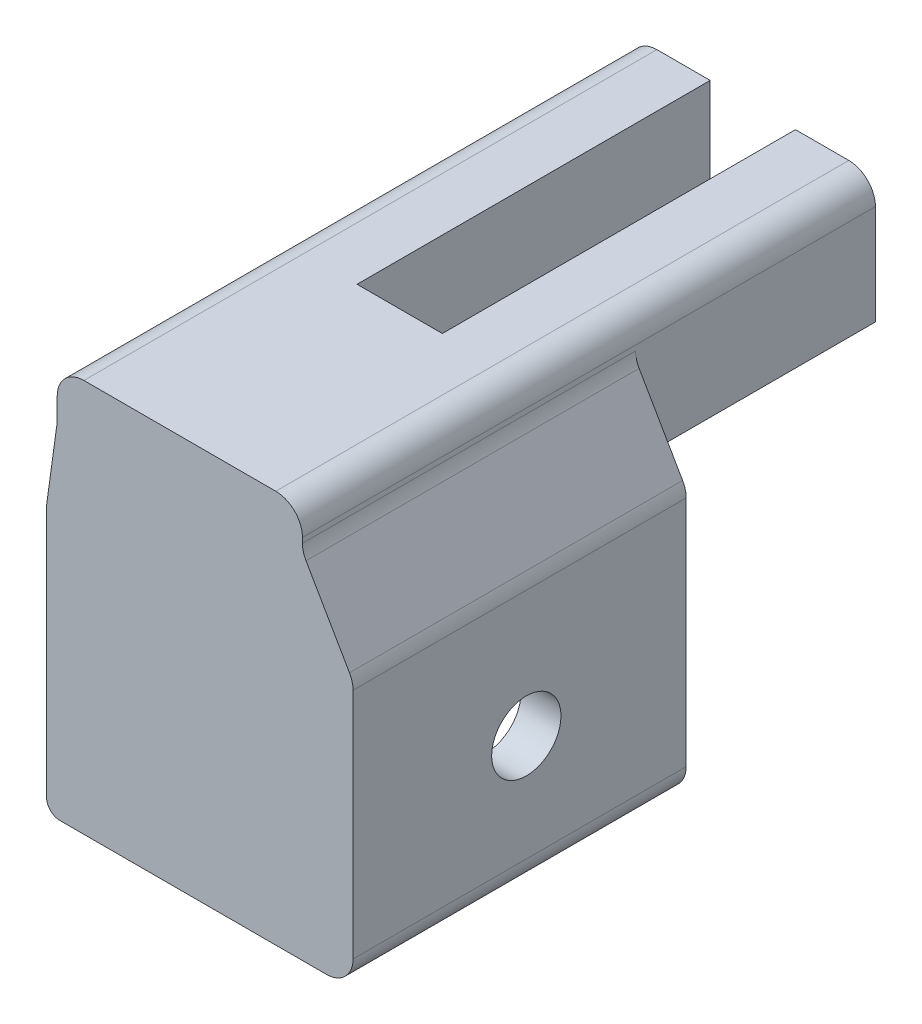
SolidWorks part; units mm, degrees
ref_plane "正面" through (0, 0, 0) normal (0, 0, 1) x (1, 0, 0)
ref_plane "平面" through (0, 0, 0) normal (0, 1, 0) x (1, 0, 0)
ref_plane "右側面" through (0, 0, 0) normal (1, 0, 0) x (0, 0, -1)
sketch "ｽｹｯﾁ1" plane through (0, 0, 0) normal (0, 0, 1) x (1, 0, 0)
  line L1 (-10, 10) -> (10, 10)
  line L2 (-10, 10) -> (-10, -10)
  line L3 (-10, -10) -> (10, -10)
  line L4 (10, 10) -> (10, -10)
  line L5 (-10, 10) -> (10, -10) construction
  line L6 (-10, -10) -> (10, 10) construction
  point P0 (0, 0)
  dimension "D1" = 20
extrude "ﾎﾞｽ - 押し出し1" add sketch "ｽｹｯﾁ1" along normal blind 3
sketch "ｽｹｯﾁ2" plane through (0, 0, 0) normal (0, 0, -1) x (-1, 0, 0)
  line L0 (-10, 10) -> (10, 10) construction
  line L1 (-3.5, 4) -> (3.5, 4)
  line L2 (-3.5, 4) -> (-3.5, 10)
  line L3 (-3.5, 10) -> (3.5, 10)
  line L4 (3.5, 4) -> (3.5, 10)
  line L5 (-3.5, 4) -> (3.5, 10) construction
  line L6 (-3.5, 10) -> (3.5, 4) construction
  line L7 (0, 0) -> (0, 7) construction
  point P0 (0, 7)
  dimension "D1" = 6
  dimension "D2" = 7
extrude "ﾎﾞｽ - 押し出し2" add sketch "ｽｹｯﾁ2" along normal blind 40
sketch "ｽｹｯﾁ3" plane through (0, 0, 3) normal (0, 0, 1) x (1, 0, 0)
  line L0 (-10, -10) -> (10, -10) construction
  line L1 (10, 10) -> (13, 10)
  line L2 (10, 10) -> (10, -10)
  line L3 (10, -10) -> (13, -10)
  line L4 (13, 10) -> (13, -10)
  dimension "D1" = 3
extrude "ﾎﾞｽ - 押し出し3" add sketch "ｽｹｯﾁ3" against normal blind 25
sketch "ｽｹｯﾁ4" plane through (13, 0, 0) normal (1, 0, 0) x (0, 0, -1)
  line L0 (0, 0) -> (22, 0) construction
  line L1 (22, -10) -> (22, 10) construction
  circle A0 centre (10, 0) radius 2.6
  dimension "D1" = 10
  dimension "D2" = 5.2
extrude "ｶｯﾄ - 押し出し1" cut sketch "ｽｹｯﾁ4" against normal up to next
fillet "ﾌｨﾚｯﾄ1" radius 1 1 edges at (-10, -10, 1.5)
ref_plane "平面1" through (0, 0, -13.5) normal (0, 0, -1) x (-1, 0, 0)
sketch "ｽｹｯﾁ5" plane through (0, 0, -13.5) normal (0, 0, -1) x (-1, 0, 0)
  line L0 (3.5, 10) -> (-3.5, 10) construction
  line L1 (-1.6, 6.1) -> (1.6, 6.1)
  line L2 (-1.6, 6.1) -> (-1.6, 10)
  line L3 (-1.6, 10) -> (1.6, 10)
  line L4 (1.6, 6.1) -> (1.6, 10)
  line L5 (-1.6, 6.1) -> (1.6, 10) construction
  line L6 (-1.6, 10) -> (1.6, 6.1) construction
  line L7 (0, 8.05) -> (0, 0) construction
  point P0 (0, 8.05)
  dimension "D1" = 3.2
  dimension "D2" = 3.9
extrude "ｶｯﾄ - 押し出し2" cut sketch "ｽｹｯﾁ5" along normal blind 30
sketch "ｽｹｯﾁ6" plane through (0, 0, 3) normal (0, 0, 1) x (1, 0, 0)
  line L0 (13, 10) -> (-10, 10) construction
  line L1 (3.2, 10) -> (9.2, 10)
  line L2 (3.2, 10) -> (3.2, 19.5)
  line L3 (3.2, 19.5) -> (9.2, 19.5)
  line L4 (9.2, 10) -> (9.2, 19.5)
  line L5 (0, 0) -> (0, 10) construction
  line L6 (-3.2, 19.5) -> (-9.2, 19.5)
  line L7 (-9.2, 10) -> (-9.2, 19.5)
  line L8 (-3.2, 10) -> (-9.2, 10)
  line L9 (-3.2, 10) -> (-3.2, 19.5)
  dimension "D1" = 6.4
  dimension "D2" = 9.5
  dimension "D3" = 6
extrude "ﾎﾞｽ - 押し出し4" add sketch "ｽｹｯﾁ6" against normal up to surface (43 mm away) up to face at (0, 7.525, -40)
chamfer "面取り1" distance 0.5 angle 45 2 edges at (-3.5, 10, -20) (3.5, 10, -20)
sketch "ｽｹｯﾁ7" plane through (0, 0, 3) normal (0, 0, 1) x (1, 0, 0)
  line L1 (-3.2, 19.5) -> (3.2, 19.5)
  line L2 (-3.2, 19.5) -> (-3.2, 10)
  line L3 (-3.2, 10) -> (3.2, 10)
  line L4 (3.2, 19.5) -> (3.2, 10)
extrude "ﾎﾞｽ - 押し出し5" add sketch "ｽｹｯﾁ7" against normal blind 16.5
sketch "ｽｹｯﾁ8" plane through (0, 0, 3) normal (0, 0, 1) x (1, 0, 0)
  line L0 (13, 10) -> (9.2, 16.5818)
  line L1 (9.2, 10) -> (9.2, 19.5) construction
  line L2 (9.2, 16.5818) -> (9.2, 10)
  line L3 (9.2, 10) -> (13, 10)
  dimension "D1" = 60
extrude "ﾎﾞｽ - 押し出し6" add sketch "ｽｹｯﾁ8" against normal up to surface (25 mm away) up to face at (11.5, 0, -22)
fillet "ﾌｨﾚｯﾄ2" radius 2 5 edges at (13, -10, -9.5) (13, 10, -9.5) (9.2, 16.5818, -9.5) (9.2, 19.5, -18.5) (-9.2, 19.5, -18.5)
sketch "ｽｹｯﾁ9" plane through (0, 0, 3) normal (0, 0, 1) x (1, 0, 0)
  line L0 (-10, 10) -> (-9.2, 15.8)
  line L1 (-9.2, 17.5) -> (-9.2, 10) construction
  line L2 (-9.2, 15.8) -> (-9.2, 10)
  line L3 (-9.2, 10) -> (-10, 10)
  dimension "D1" = 5.8
extrude "ﾎﾞｽ - 押し出し7" add sketch "ｽｹｯﾁ9" against normal up to surface (43 mm away) up to face at (0, 11.6514, -40)
sketch "ｽｹｯﾁ10" plane through (0, 0, -40) normal (0, 0, -1) x (-1, 0, 0)
  line L0 (3.5, 4) -> (3.5, 9.5) construction
  line L1 (1.6, 6.1) -> (3.5, 6.1)
  line L2 (1.6, 6.1) -> (1.6, 8.1)
  line L3 (1.6, 8.1) -> (3.5, 8.1)
  line L4 (3.5, 6.1) -> (3.5, 8.1)
  dimension "D1" = 2
extrude "ｶｯﾄ - 押し出し3" cut sketch "ｽｹｯﾁ10" against normal up to surface (26.5 mm away) up to face at (0, 11.4, -13.5)
fillet "ﾌｨﾚｯﾄ3" radius 0.5 2 edges at (-3.5, 8.1, -26.75) (-3.5, 6.1, -26.75)
fillet "ﾌｨﾚｯﾄ4" radius 1.5 2 edges at (3.5, 4, -20) (-3.5, 4, -20)
